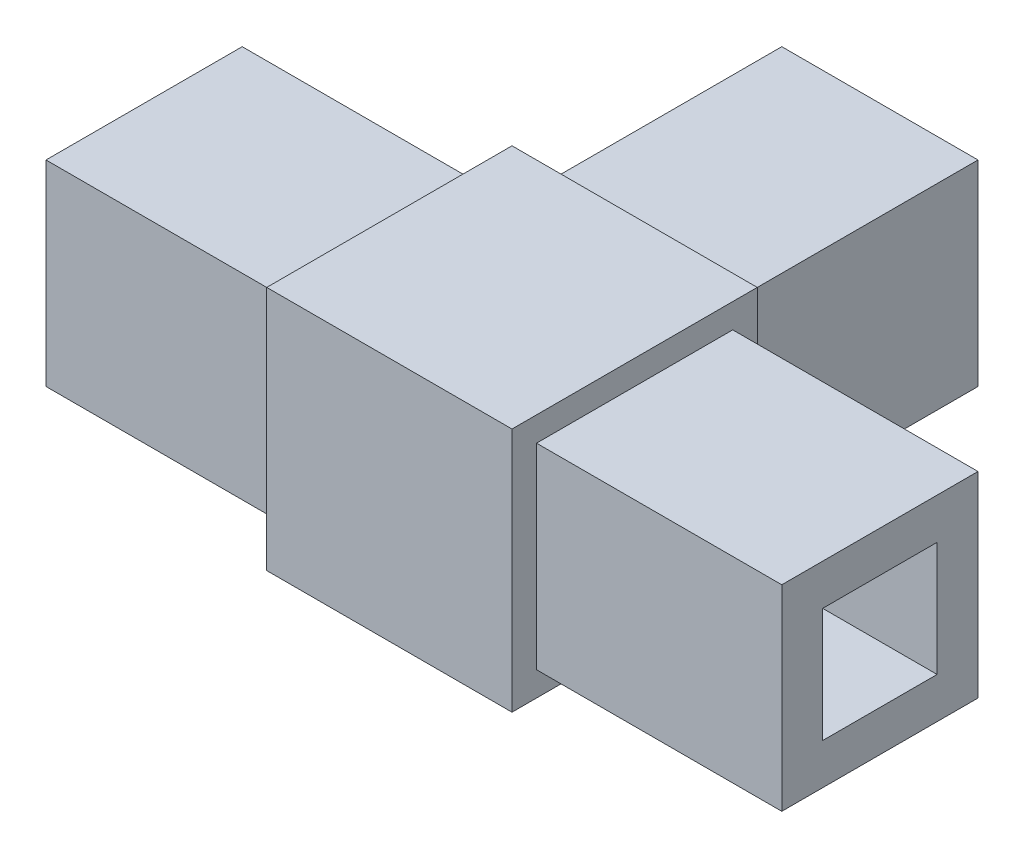
SolidWorks part; units mm, degrees
ref_plane "Alzado" through (0, 0, 0) normal (0, 0, 1) x (1, 0, 0)
ref_plane "Planta" through (0, 0, 0) normal (0, 1, 0) x (1, 0, 0)
ref_plane "Vista lateral" through (0, 0, 0) normal (1, 0, 0) x (0, 0, -1)
sketch "Croquis1" plane through (0, 0, 0) normal (0, 1, 0) x (1, 0, 0)
  line L1 (15, -15) -> (-15, -15)
  line L2 (15, -15) -> (15, 15)
  line L3 (15, 15) -> (-15, 15)
  line L4 (-15, -15) -> (-15, 15)
  line L5 (15, -15) -> (-15, 15) construction
  line L6 (15, 15) -> (-15, -15) construction
  line L7 (15, -15) -> (45, -15)
  line L8 (15, -15) -> (15, 15)
  line L9 (15, 15) -> (45, 15)
  line L10 (45, -15) -> (45, 15)
  line L11 (-15, 15) -> (15, 15)
  line L12 (-15, 15) -> (-15, 45)
  line L13 (-15, 45) -> (15, 45)
  line L14 (15, 15) -> (15, 45)
  line L15 (-15, -15) -> (-45, -15)
  line L16 (-15, -15) -> (-15, 15)
  line L17 (-15, 15) -> (-45, 15)
  line L18 (-45, -15) -> (-45, 15)
  point P0 (0, 0)
  dimension "D1" = 30
  dimension "D2" = 30
  dimension "D3" = 30
  dimension "D4" = 30
  dimension "D5" = 30
extrude "Extruir1" add sketch "Croquis1" along normal blind 30 contours L3 L14 L13 L12 | L4 L1 L2 L3 | L7 L10 L9 L2 | L18 L15 L4 L17
sketch "Croquis2" plane through (45, 0, 0) normal (1, 0, 0) x (0, 0, -1)
  line L4 (-15, 0) -> (15, 0)
  line L5 (15, 0) -> (15, 30)
  line L6 (15, 30) -> (-15, 30)
  line L7 (-15, 30) -> (-15, 0)
  line L8 (-15, 0) -> (15, 0)
  line L9 (15, 0) -> (15, 30)
  line L10 (15, 30) -> (-15, 30)
  line L11 (-15, 30) -> (-15, 0)
  line L16 (-12, 3) -> (12, 3)
  line L17 (12, 3) -> (12, 27)
  line L18 (12, 27) -> (-12, 27)
  line L19 (-12, 27) -> (-12, 3)
  line L20 (-12, 3) -> (12, 3)
  line L21 (12, 3) -> (12, 27)
  line L22 (12, 27) -> (-12, 27)
  line L23 (-12, 27) -> (-12, 3)
  dimension "D1" = 0
  dimension "D2" = 3
extrude "Extruir2" cut sketch "Croquis2" against normal blind 30
sketch "Croquis3" plane through (0, 0, -45) normal (0, 0, -1) x (-1, 0, 0)
  line L0 (-12, 3) -> (12, 3)
  line L1 (12, 3) -> (12, 27)
  line L2 (12, 27) -> (-12, 27)
  line L3 (-12, 27) -> (-12, 3)
  line L4 (-15, 0) -> (15, 0)
  line L5 (15, 0) -> (15, 30)
  line L6 (15, 30) -> (-15, 30)
  line L7 (-15, 30) -> (-15, 0)
  line L8 (-15, 0) -> (15, 0)
  line L9 (15, 0) -> (15, 30)
  line L10 (15, 30) -> (-15, 30)
  line L11 (-15, 30) -> (-15, 0)
  line L16 (15, 0) -> (15, 30) construction
  dimension "D1" = 0
  dimension "D2" = 3
extrude "Extruir3" cut sketch "Croquis3" against normal blind 30
sketch "Croquis5" plane through (-45, 0, 0) normal (-1, 0, 0) x (0, 0, 1)
  line L0 (-12, 3) -> (12, 3)
  line L1 (12, 3) -> (12, 27)
  line L2 (12, 27) -> (-12, 27)
  line L3 (-12, 27) -> (-12, 3)
  line L4 (-15, 0) -> (15, 0)
  line L5 (15, 0) -> (15, 30)
  line L6 (15, 30) -> (-15, 30)
  line L7 (-15, 30) -> (-15, 0)
  line L8 (-15, 0) -> (15, 0)
  line L9 (15, 0) -> (15, 30)
  line L10 (15, 30) -> (-15, 30)
  line L11 (-15, 30) -> (-15, 0)
  dimension "D1" = 0
  dimension "D2" = 3
extrude "Extruir4" cut sketch "Croquis5" against normal blind 30
shell "Vaciado1" thickness 5
